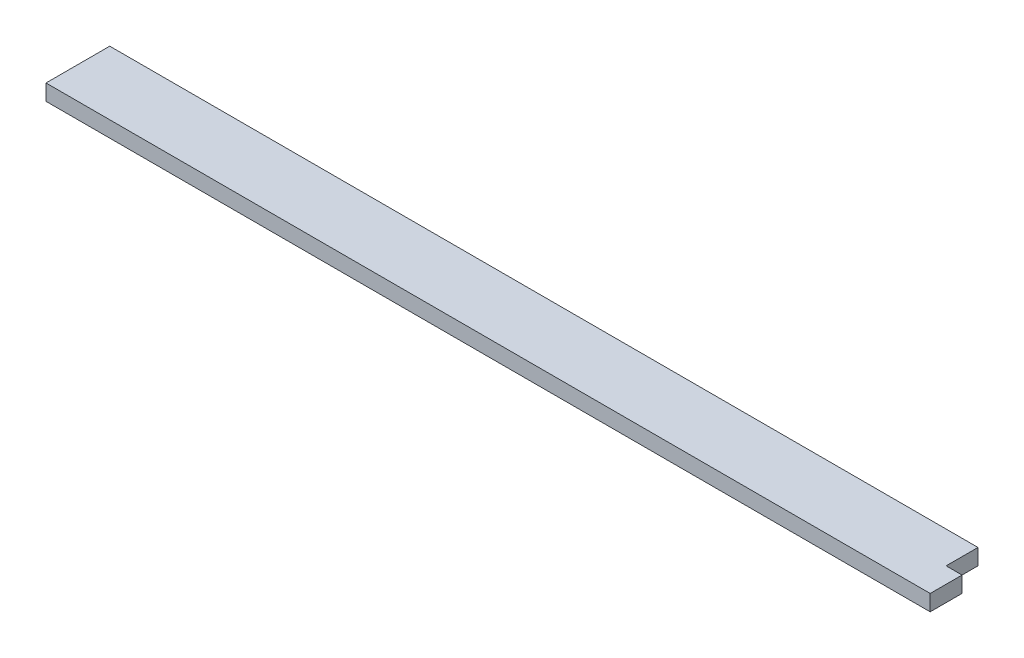
SolidWorks part; units mm, degrees
ref_plane "Front Plane" through (0, 0, 0) normal (0, 0, 1) x (1, 0, 0)
ref_plane "Top Plane" through (0, 0, 0) normal (0, 1, 0) x (1, 0, 0)
ref_plane "Right Plane" through (0, 0, 0) normal (1, 0, 0) x (0, 0, -1)
sketch "Sketch1" plane through (0, 0, 0) normal (0, 1, 0) x (1, 0, 0)
  line L0 (84.8995, 6.35) -> (84.8995, 0)
  line L1 (-88.0745, 6.35) -> (84.8995, 6.35)
  line L2 (-88.0745, 6.35) -> (-88.0745, -6.35)
  line L3 (-88.0745, -6.35) -> (88.0745, -6.35)
  line L4 (88.0745, 0) -> (88.0745, -6.35)
  line L5 (84.8995, 0) -> (88.0745, 0)
  dimension "D3" = 3.175
extrude "Boss-Extrude1" add sketch "Sketch1" along normal blind 3.175
